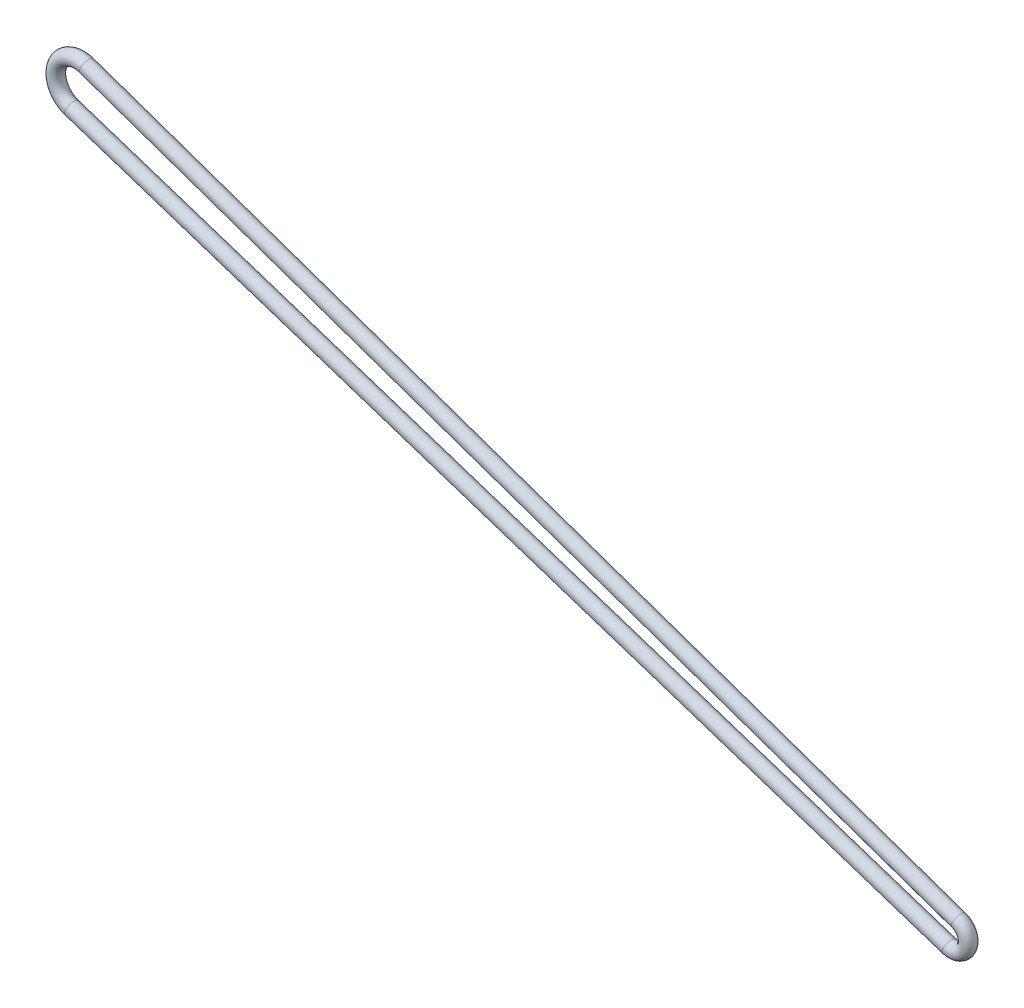
SolidWorks part; units mm, degrees
ref_plane "前视基准面" through (0, 0, 0) normal (0, 0, 1) x (1, 0, 0)
ref_plane "上视基准面" through (0, 0, 0) normal (0, 1, 0) x (1, 0, 0)
ref_plane "右视基准面" through (0, 0, 0) normal (1, 0, 0) x (0, 0, -1)
sketch "草图2" plane through (0, 0, 0) normal (0, 0, 1) x (1, 0, 0)
  line L0 (0, 0) -> (1, 0) construction
  line L1 (0, 0) -> (0, 1) construction
  line L2 (293.7427, 74.3638) -> (104.2819, 136.3937)
  line L3 (107.4837, 145.8667) -> (295.7278, 80.2371)
  arc A0 (295.7278, 80.2371) -> (293.7427, 74.3638) centre (294.7073, 77.3099) cw
  arc A1 (104.2819, 136.3937) -> (107.4837, 145.8667) centre (105.8377, 141.1455) cw
sweep "扫描19" add path "草图2" circular profile diameter 3 parameters "D3"=3
